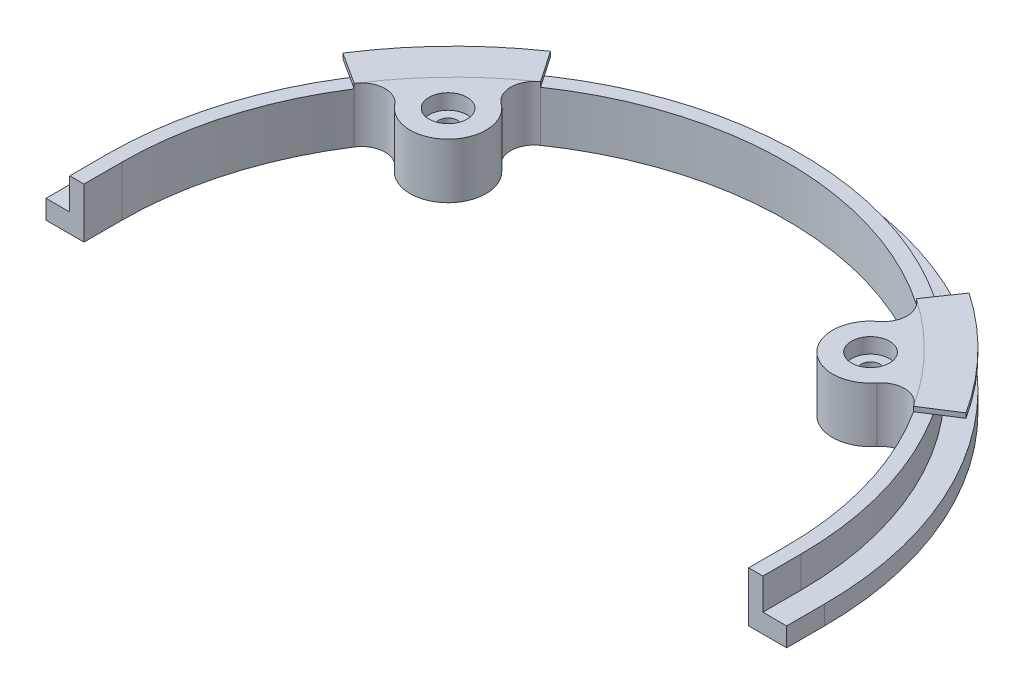
SolidWorks part; units mm, degrees
material "Aluminum"
ref_plane "Front Plane" through (0, 0, 0) normal (0, 0, 1) x (1, 0, 0)
ref_plane "Top Plane" through (0, 0, 0) normal (0, 1, 0) x (1, 0, 0)
ref_plane "Right Plane" through (0, 0, 0) normal (1, 0, 0) x (0, 0, -1)
sketch "Sketch1" plane through (0, 0, 0) normal (0, 1, 0) x (1, 0, 0)
  line L0 (36.5, 0) -> (36.5, -4)
  line L1 (-36.5, 0) -> (-36.5, -4)
  line L2 (-36.5, -4) -> (-35, -4)
  line L3 (35, -4) -> (36.5, -4)
  line L7 (35, 0) -> (35, -4)
  line L8 (-35, 0) -> (-35, -4)
  arc A0 (-35, 0) -> (35, 0) centre (0, 0) cw
  arc A1 (-36.5, 0) -> (36.5, 0) centre (0, 0) cw
  point P0 (0, 0)
  dimension "D2" = 35
  dimension "D1" = 1.5
  dimension "D3" = 4
  dimension "D4" = 4
extrude "Boss-Extrude1" add sketch "Sketch1" along normal blind 3.3
sketch "Sketch2" plane through (0, 0, 0) normal (0, -1, 0) x (1, 0, 0)
  line L0 (-35, 4) -> (-39, 4)
  line L1 (-35, 4) -> (-35, 0) construction
  line L2 (35, 0) -> (35, 4) construction
  line L3 (35, 4) -> (39, 4)
  line L4 (-39, 0) -> (-39, 4)
  line L5 (39, 0) -> (39, 4)
  line L7 (-39, 0) -> (-39, 0)
  line L8 (-36.5, 4) -> (-35, 4) construction
  line L9 (35, 4) -> (36.5, 4) construction
  line L10 (-35, 4) -> (-35, 0)
  line L11 (35, 4) -> (35, 0)
  line L12 (-39, 0) -> (-39, 0)
  line L14 (39, 0) -> (39, 0)
  line L16 (-66.2881, 0) -> (-39, 0) construction
  line L17 (39, 0) -> (65.7284, 0) construction
  line L18 (-66.2881, 4) -> (-39, 4) construction
  line L19 (39, 4) -> (65.7284, 4) construction
  line L20 (39, 0) -> (39, 0) construction
  arc A0 (-35, 0) -> (35, 0) centre (0, 0) ccw
  arc A1 (-39, 0) -> (39, 0) centre (0, 0) ccw
  arc M1 (-36.5, 0) -> (36.5, 0) centre (0, 0) ccw
  line M2 (36.5, 0) -> (36.5, 4)
  line M3 (36.5, 4) -> (35, 4)
  line M4 (35, 4) -> (35, 0)
  arc M5 (35, 0) -> (-35, 0) centre (0, 0) cw
  line M6 (-35, 0) -> (-35, 4)
  line M7 (-35, 4) -> (-36.5, 4)
  line M8 (-36.5, 4) -> (-36.5, 0)
  dimension "D1" = 4
  dimension "D2" = 4
  dimension "D4" = 4
extrude "Boss-Extrude2" add sketch "Sketch2" along normal blind 2 separate body contours L4 A1 L5 L3 L0 M2 M1 M8 | M8 M1 M2 M3 M4 M5 M6 M7
sketch "Sketch3" plane through (0, 3.3, 0) normal (0, 1, 0) x (1, 0, 0)
  line L0 (0, 0) -> (0, 40.1247) construction
  line L1 (0, 0) -> (-34, 33) construction
  arc A0 (-25.3842, 19.1117) -> (-19.8608, 24.8025) centre (-22.245, 21.5907) ccw
  arc A1 (35, 0) -> (-35, 0) centre (0, 0) ccw construction
  arc A2 (-29.4497, 18.9133) -> (-19.7838, 28.8722) centre (0, 0) cw
  arc A3 (-25.3842, 19.1117) -> (-29.4497, 18.9133) centre (-27.3462, 17.5623) ccw
  arc A4 (-19.8608, 24.8025) -> (-19.7838, 28.8722) centre (-18.3706, 26.8099) cw
  arc A5 (-25.3842, 19.1117) -> (-29.4497, 18.9133) centre (-27.3462, 17.5623) ccw
  arc A6 (-19.8608, 24.8025) -> (-19.7838, 28.8722) centre (-18.3706, 26.8099) cw
  arc A7 (19.8608, 24.8025) -> (19.7838, 28.8722) centre (18.3706, 26.8099) ccw
  arc A8 (25.3842, 19.1117) -> (29.4497, 18.9133) centre (27.3462, 17.5623) cw
  arc A9 (19.8608, 24.8025) -> (19.7838, 28.8722) centre (18.3706, 26.8099) ccw
  arc A10 (25.3842, 19.1117) -> (29.4497, 18.9133) centre (27.3462, 17.5623) cw
  arc A11 (29.4497, 18.9133) -> (19.7838, 28.8722) centre (0, 0) ccw
  arc A12 (25.3842, 19.1117) -> (19.8608, 24.8025) centre (22.245, 21.5907) cw
  arc M5 (-35, 0) -> (35, 0) centre (0, 0) cw
  dimension "D1" = 8
  dimension "D2" = 2.5
extrude "Boss-Extrude3" add sketch "Sketch3" against normal blind 5.3 and the other way blind 0.5 contours A0 A4 A3 M5 | A12 A8 A7 M5
sketch "Sketch9" plane through (0, 3.3, 0) normal (0, 1, 0) x (1, 0, 0)
  line L0 (0, 0) -> (0, 35) construction
  line L1 (0, 0) -> (-22.2739, 22.2739) construction
  line L2 (-29.4497, 18.9133) -> (-32.8154, 21.0748)
  line L3 (-19.7838, 28.8722) -> (-22.0448, 32.1718)
  line L4 (29.4497, 18.9133) -> (32.8154, 21.0748)
  line L5 (19.7838, 28.8722) -> (22.0448, 32.1718)
  arc A0 (19.7838, 28.8722) -> (-19.7838, 28.8722) centre (0, 0) ccw construction
  arc A2 (-29.4497, 18.9133) -> (-19.7838, 28.8722) centre (0, 0) cw
  arc A3 (-32.8154, 21.0748) -> (-22.0448, 32.1718) centre (0, 0) cw
  arc A4 (22.0448, 32.1718) -> (32.8154, 21.0748) centre (0, 0) cw
  arc A5 (-35, 0) -> (35, 0) centre (0, 0) cw construction
  arc A6 (-39, 0) -> (39, 0) centre (0, 0) cw construction
  arc A7 (0, 35) -> (29.4497, 18.9133) centre (0, 0) cw
  arc A8 (-29.4497, 18.9133) -> (-19.7838, 28.8722) centre (0, 0) cw
  arc M3 (36.5, 0) -> (-36.5, 0) centre (0, 0) ccw
  dimension "D1" = 4
extrude "Boss-Extrude4" add sketch "Sketch9" along normal blind 0.5 separate body contours A3 L2 L3 M3 | L2 A2 L3 M3 | L5 A7 L4 M3 | A4 L5 L4 M3
hole_wizard "CBORE for M2 Pan Head Screw2" positions "Sketch12" profile "Sketch11" counterbore size "M2" standard "ISO"
sketch "Sketch12" plane through (0, 3.8, 0) normal (0, 1, 0) x (1, 0, 0)
  point P0 (-22.245, 21.5907)
  point P3 (22.245, 21.5907)
sketch "Sketch11" plane through (-22.245, 3.8, -21.5907) normal (1, 0, 0) x (0, 0, 1)
  line L0 (0, 0) -> (0, 30.6009)
  line L1 (0, 30.6009) -> (1, 30)
  line L2 (1, 30) -> (1, 1.6)
  line L3 (1, 1.6) -> (2, 1.6)
  line L4 (2, 1.6) -> (2, 0)
  line L5 (2, 0) -> (0, 0)
  line L10 (0, 30.6009) -> (-1, 30) construction
  line L11 (0, -6.35) -> (0, 107.95) construction
  dimension "Hole Dia." = 2
  dimension "Hole Depth" = 30
  dimension "C'Bore Dia." = 4
  dimension "C'Bore Depth" = 1.6
  dimension "Drill Angle" = 118
